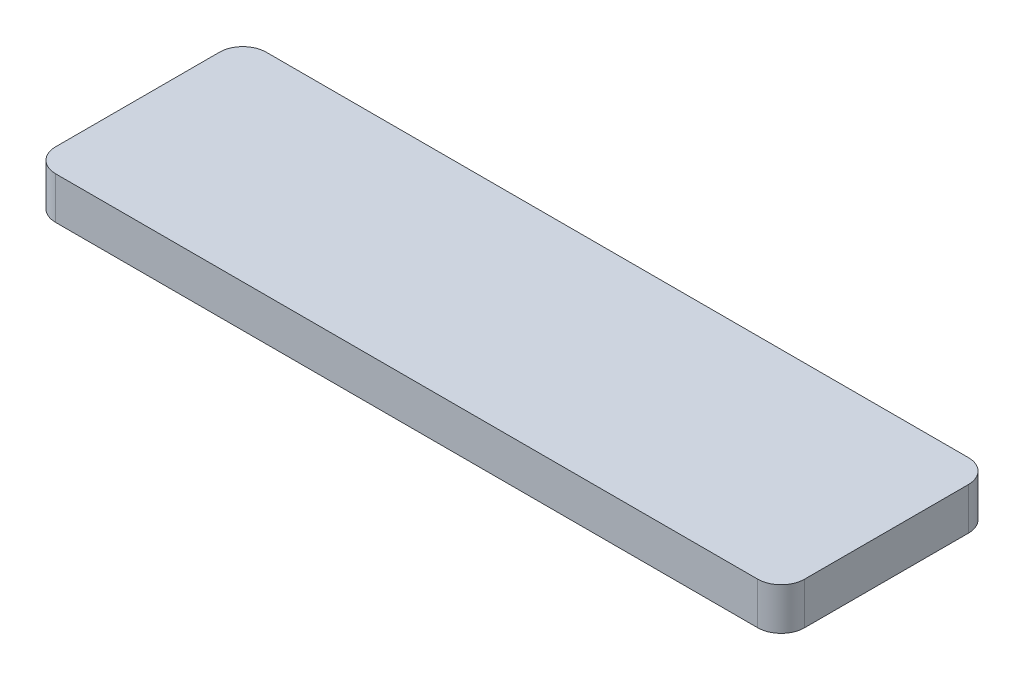
SolidWorks part; units mm, degrees
ref_plane "前视基准面" through (0, 0, 0) normal (0, 0, 1) x (1, 0, 0)
ref_plane "上视基准面" through (0, 0, 0) normal (0, 1, 0) x (1, 0, 0)
ref_plane "右视基准面" through (0, 0, 0) normal (1, 0, 0) x (0, 0, -1)
other "Configuration Table"
sketch "草图1" plane through (0, 0, 0) normal (0, 1, 0) x (1, 0, 0)
  line L1 (-160, -45) -> (160, -45)
  line L2 (-160, -45) -> (-160, 45)
  line L3 (-160, 45) -> (160, 45)
  line L4 (160, -45) -> (160, 45)
  point P4 (-160, 0)
  point P6 (0, 45)
  dimension "D1" = 90
  dimension "D2" = 320
extrude "凸台-拉伸1" add sketch "草图1" along normal blind 18
fillet "圆角1" radius 10 4 edges at (-160, 9, -45) (160, 9, -45) (160, 9, 45) (-160, 9, 45)
